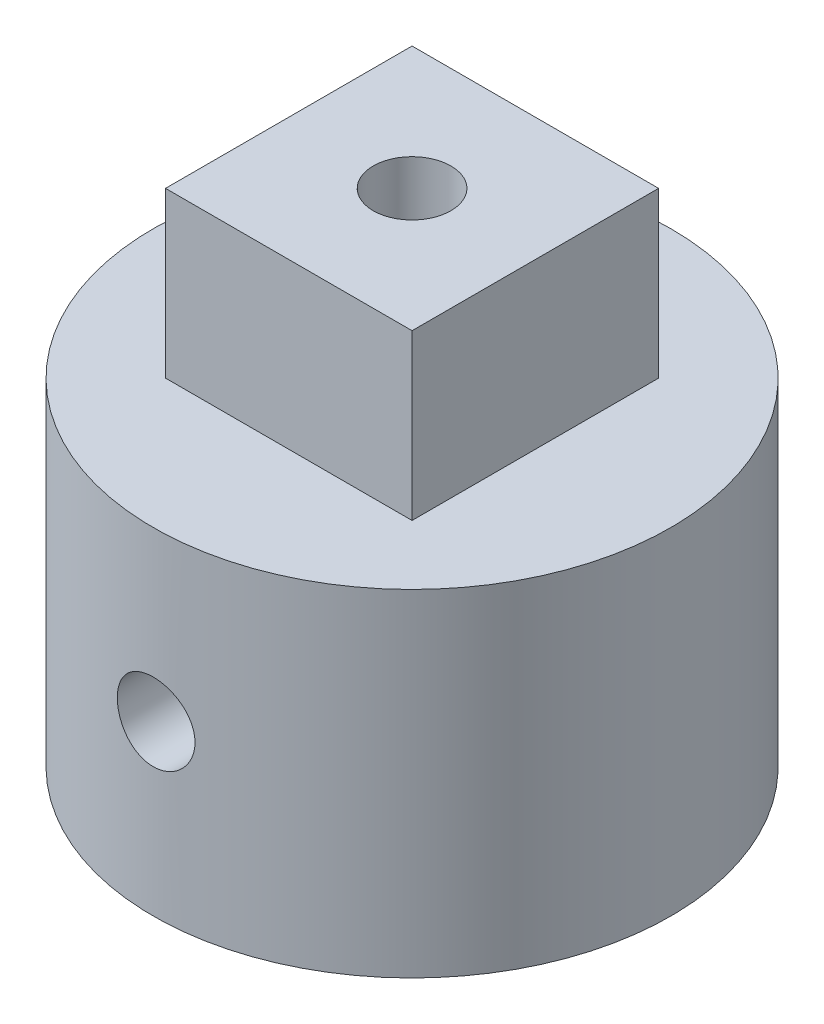
SolidWorks part; units mm, degrees
material "PUR"
ref_plane "Front Plane" through (0, 0, 0) normal (0, 0, 1) x (1, 0, 0)
ref_plane "Top Plane" through (0, 0, 0) normal (0, 1, 0) x (1, 0, 0)
ref_plane "Right Plane" through (0, 0, 0) normal (1, 0, 0) x (0, 0, -1)
sketch "Sketch1" plane through (0, 0, 0) normal (0, 1, 0) x (1, 0, 0)
  line L0 (-4.7625, -4.7625) -> (4.7625, -4.7625)
  line L1 (-4.7625, -4.7625) -> (-4.7625, 4.7625)
  line L2 (4.7625, -4.7625) -> (4.7625, 4.7625)
  line L3 (-4.7625, 4.7625) -> (4.7625, 4.7625)
  line L4 (-4.7625, -4.7625) -> (4.7625, 4.7625) construction
  line L5 (4.7625, -4.7625) -> (-4.7625, 4.7625) construction
  circle A0 centre (0, 0) radius 1.5
  point P1 (0, 0)
  dimension "D2" = 3
  dimension "D1" = 9.525
extrude "Boss-Extrude1" add sketch "Sketch1" along normal blind 6.35
sketch "Sketch2" plane through (0, 0, 0) normal (0, -1, 0) x (1, 0, 0)
  circle A0 centre (0, 0) radius 10
  dimension "D1" = 20
extrude "Boss-Extrude2" add sketch "Sketch2" along normal blind 13
sketch "Sketch3" plane through (0, -13, 0) normal (0, -1, 0) x (1, 0, 0)
  circle A0 centre (0, 0) radius 1.55
  dimension "D1" = 3.1
extrude "Cut-Extrude1" cut sketch "Sketch3" against normal blind 11
sketch "Sketch5" plane through (0, 0, 0) normal (0, 0, 1) x (1, 0, 0)
  line L0 (0, 0) -> (0, -13) construction
  line L1 (-10, -13) -> (10, -13) construction
  circle A0 centre (0, -6.5) radius 1.5
  point P2 (0, 0)
  point P8 (0, -6.5)
  dimension "D1" = 3
extrude "Cut-Extrude2" cut sketch "Sketch5" against normal mid plane 20 contours A0
